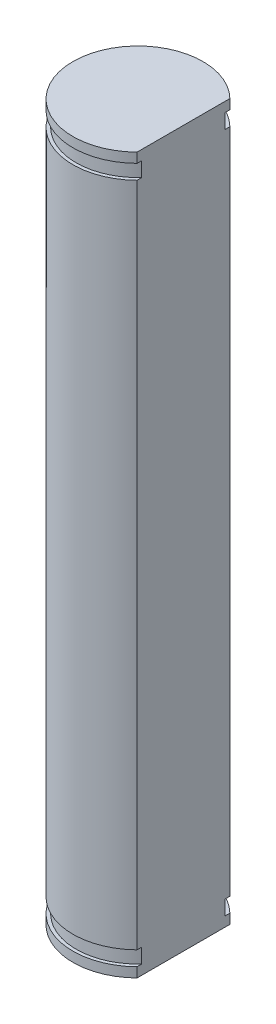
SolidWorks part; units mm, degrees
ref_plane "Front Plane" through (0, 0, 0) normal (0, 0, 1) x (1, 0, 0)
ref_plane "Top Plane" through (0, 0, 0) normal (0, 1, 0) x (1, 0, 0)
ref_plane "Right Plane" through (0, 0, 0) normal (1, 0, 0) x (0, 0, -1)
sketch "Sketch1" plane through (0, 0, 0) normal (0, 0, 1) x (1, 0, 0)
  line L0 (0, 0) -> (-4, 0)
  line L1 (-4, 0) -> (-4, -0.6)
  line L2 (-4, -0.6) -> (-3.8, -0.6)
  line L3 (-3.8, -0.6) -> (-3.8, -1.5)
  line L4 (-3.8, -1.5) -> (-4, -1.5)
  line L5 (-4, -1.5) -> (-4, -42.5)
  line L6 (-4, -42.5) -> (-3.8, -42.5)
  line L7 (-3.8, -42.5) -> (-3.8, -43.4)
  line L8 (-3.8, -43.4) -> (-4, -43.4)
  line L9 (-4, -43.4) -> (-4, -44)
  line L10 (-4, -44) -> (0, -44)
  line L11 (0, -44) -> (0, 0)
  dimension "D1" = 41
  dimension "D2" = 0.6
  dimension "D3" = 0.9
  dimension "D4" = 4
  dimension "D5" = 3.8
revolve "Revolve1" add sketch "Sketch1" angle 360 about L11
sketch "Sketch2" plane through (0, 0, 0) normal (0, 1, 0) x (1, 0, 0)
  line L0 (2.8, -2.8566) -> (2.8, 2.8566)
  line L1 (2.8, 0) -> (4, 0) construction
  circle A0 centre (0, 0) radius 4 construction
  circle A1 centre (0, 0) radius 4 construction
  arc A2 (2.8, 2.8566) -> (2.8, -2.8566) centre (0, 0) cw
  dimension "D1" = 1.2
extrude "Cut-Extrude1" cut sketch "Sketch2" against normal through all
